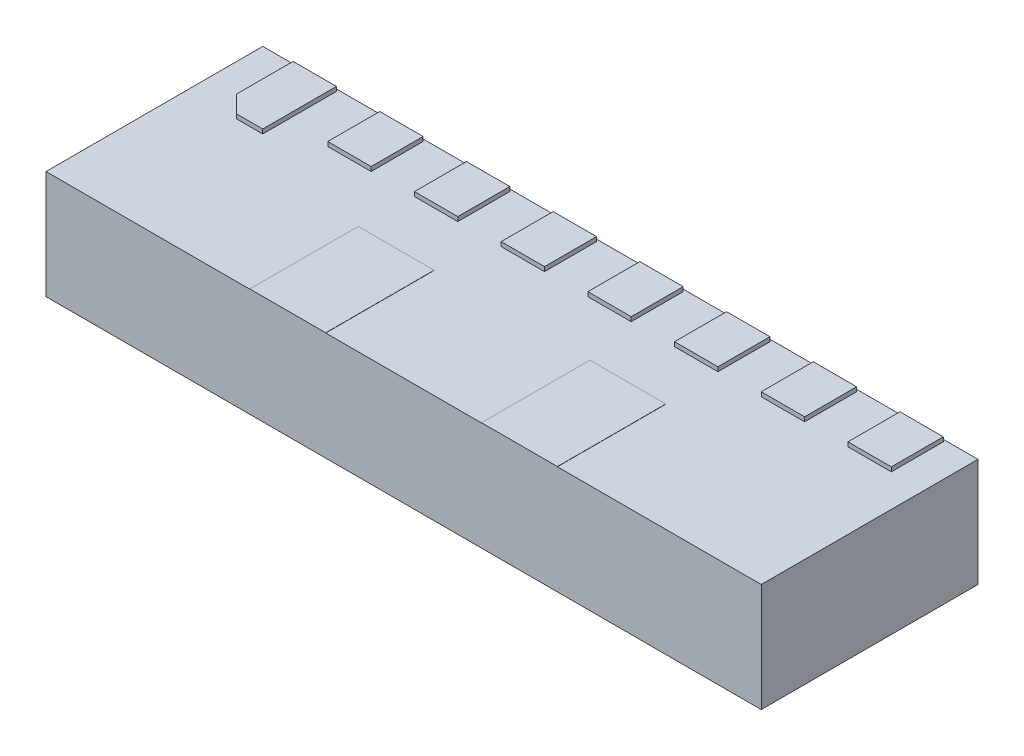
SolidWorks part; units mm, degrees
ref_plane "Front Plane" through (0, 0, 0) normal (0, 0, 1) x (1, 0, 0)
ref_plane "Top Plane" through (0, 0, 0) normal (0, 1, 0) x (1, 0, 0)
ref_plane "Right Plane" through (0, 0, 0) normal (1, 0, 0) x (0, 0, -1)
sketch "Sketch1" plane through (0, 0, 0) normal (0, 1, 0) x (1, 0, 0)
  line L1 (-1.65, 0.5) -> (1.65, 0.5)
  line L2 (-1.65, 0.5) -> (-1.65, -0.5)
  line L3 (-1.65, -0.5) -> (1.65, -0.5)
  line L4 (1.65, 0.5) -> (1.65, -0.5)
  line L5 (-1.65, 0.5) -> (1.65, -0.5) construction
  line L6 (-1.65, -0.5) -> (1.65, 0.5) construction
  point P0 (0, 0)
  dimension "D1" = 3.3
  dimension "D2" = 1
extrude "Boss-Extrude1" add sketch "Sketch1" along normal blind 0.5
sketch "Sketch2" plane through (0, 0.5, 0) normal (0, 1, 0) x (1, 0, 0)
  line L0 (0, 1.1724) -> (0, -1.0782) construction
  line L1 (-2.0344, 0) -> (2.5888, 0) construction
  line L2 (-1.65, -0.5) -> (1.65, -0.5) construction
  line L3 (-1.65, -0.5) -> (1.65, -0.5) construction
  line L4 (-0.595, 0.7012) -> (-0.595, -1.0172) construction
  line L5 (0.595, 0.7012) -> (0.595, -0.5257) construction
  line L6 (0.3594, -0.5) -> (0.7094, -0.5)
  line L7 (-0.7094, -0.5) -> (-0.7094, 0)
  line L8 (0.3594, -0.5) -> (0.3594, 0)
  line L9 (0.3594, 0) -> (0.7094, 0)
  line L10 (0.7094, -0.5) -> (0.7094, 0)
  line L11 (0.5835, -0.5) -> (0.7094, 0) construction
  line L12 (0.3594, 0) -> (0.595, -0.5257) construction
  line L13 (-0.3594, -0.5) -> (-0.7094, -0.5)
  line L14 (-0.3594, -0.5) -> (-0.3594, 0)
  line L15 (-0.3594, 0) -> (-0.7094, 0)
  point P11 (0.5835, -0.5)
  dimension "D1" = 0.5
  dimension "D2" = 0.595
  dimension "D3" = 0.595
  dimension "D4" = 0.35
extrude "Boss-Extrude2" add sketch "Sketch2" along normal blind 0.001
sketch "Sketch3" plane through (0, 0.5, 0) normal (0, 1, 0) x (1, 0, 0)
  line L0 (0, 1.0726) -> (0, -1.178) construction
  line L1 (-2.0289, 0) -> (2.2229, 0) construction
  line L2 (0.5, 0.49) -> (0.7, 0.49)
  line L3 (0.1, 0.49) -> (0.3, 0.49)
  line L4 (0.1, 0.49) -> (0.1, 0.25)
  line L5 (0.1, 0.25) -> (0.3, 0.25)
  line L6 (0.3, 0.49) -> (0.3, 0.25)
  line L7 (0.2, 0.6575) -> (0.2, 0.2208) construction
  line L8 (1.65, 0.5) -> (-1.65, 0.5) construction
  line L9 (0.7, 0.49) -> (0.7, 0.25)
  line L10 (0.5, 0.25) -> (0.7, 0.25)
  line L11 (0.5, 0.49) -> (0.5, 0.25)
  line L12 (0.9, 0.49) -> (1.1, 0.49)
  line L13 (1.1, 0.49) -> (1.1, 0.25)
  line L14 (0.9, 0.25) -> (1.1, 0.25)
  line L15 (0.9, 0.49) -> (0.9, 0.25)
  line L16 (1.3, 0.49) -> (1.5, 0.49)
  line L17 (1.5, 0.49) -> (1.5, 0.25)
  line L18 (1.3, 0.25) -> (1.5, 0.25)
  line L19 (1.3, 0.49) -> (1.3, 0.25)
  line L20 (-0.1, 0.49) -> (-0.1, 0.25)
  line L21 (-0.1, 0.49) -> (-0.3, 0.49)
  line L22 (-0.3, 0.49) -> (-0.3, 0.25)
  line L23 (-0.1, 0.25) -> (-0.3, 0.25)
  line L24 (-0.2, 0.6063) -> (-0.2, 0.1221) construction
  line L25 (-0.5, 0.49) -> (-0.7, 0.49)
  line L26 (-0.5, 0.49) -> (-0.5, 0.25)
  line L27 (-0.5, 0.25) -> (-0.7, 0.25)
  line L28 (-0.7, 0.49) -> (-0.7, 0.25)
  line L29 (-0.9, 0.49) -> (-1.1, 0.49)
  line L30 (-0.9, 0.49) -> (-0.9, 0.25)
  line L31 (-0.9, 0.25) -> (-1.1, 0.25)
  line L32 (-1.1, 0.49) -> (-1.1, 0.25)
  point P11 (0.2, 0.49)
  dimension "D1" = 0.2
  dimension "D2" = 0.25
  dimension "D3" = 0.01
  dimension "D4" = 0.2
  dimension "D6" = 3
  dimension "D5" = 4
extrude "Boss-Extrude3" add sketch "Sketch3" along normal blind 0.02
sketch "Sketch4" plane through (0, 0.5, 0) normal (0, 1, 0) x (1, 0, 0)
  line L0 (0, 0.8382) -> (0, -0.7912) construction
sketch "Sketch5" plane through (0, 0.52, 0) normal (0, 1, 0) x (1, 0, 0)
  line L0 (-1, 0.7346) -> (-1, -0.0406) construction
sketch "Sketch6" plane through (0, 0.5, 0) normal (0, 1, 0) x (1, 0, 0)
  line L0 (-1.4, 0.7103) -> (-1.4, -0.249) construction
  line L1 (-1.5, 0.49) -> (-1.3, 0.49)
  line L2 (-1.5, 0.49) -> (-1.5, 0.2297)
  line L3 (-1.4203, 0.15) -> (-1.3, 0.15)
  line L4 (-1.3, 0.49) -> (-1.3, 0.15)
  line L5 (-1, 0.7346) -> (-1, -0.0406) construction
  line L6 (1.65, 0.5) -> (-1.65, 0.5) construction
  line L7 (-1.5, 0.2297) -> (-1.4203, 0.15)
  point P8 (-1.4, 0.49)
  dimension "D1" = 0.4
  dimension "D2" = 45
  dimension "D3" = 0.01
  dimension "D4" = 0.35
  dimension "D5" = 0.2
extrude "Boss-Extrude4" add sketch "Sketch6" along normal blind 0.02
sketch "Sketch11" plane through (0, 0, -0.5) normal (0, 0, -1) x (-1, 0, 0)
  line L2 (0.1, 0.52) -> (0.3, 0.52) construction
  line L3 (0.1, 0.495) -> (0.3, 0.495)
  line L4 (0.1, 0.495) -> (0.1, 0.39)
  line L5 (0.1, 0.39) -> (0.3, 0.39)
  line L6 (0.3, 0.495) -> (0.3, 0.39)
  line L7 (0, -0.1597) -> (0, 1.0598) construction
  line L8 (-0.3, 0.495) -> (-0.3, 0.39)
  line L9 (-0.1, 0.39) -> (-0.3, 0.39)
  line L10 (-0.1, 0.495) -> (-0.1, 0.39)
  line L11 (-0.1, 0.495) -> (-0.3, 0.495)
  line L12 (0.5, 0.495) -> (0.7, 0.495)
  line L13 (0.7, 0.495) -> (0.7, 0.39)
  line L14 (0.5, 0.39) -> (0.7, 0.39)
  line L15 (0.5, 0.495) -> (0.5, 0.39)
  line L16 (0.9, 0.495) -> (1.1, 0.495)
  line L17 (1.1, 0.495) -> (1.1, 0.39)
  line L18 (0.9, 0.39) -> (1.1, 0.39)
  line L19 (0.9, 0.495) -> (0.9, 0.39)
  line L20 (1.3, 0.495) -> (1.5, 0.495)
  line L21 (1.5, 0.495) -> (1.5, 0.39)
  line L22 (1.3, 0.39) -> (1.5, 0.39)
  line L23 (1.3, 0.495) -> (1.3, 0.39)
  line L24 (-0.5, 0.495) -> (-0.7, 0.495)
  line L25 (-0.7, 0.495) -> (-0.7, 0.39)
  line L26 (-0.5, 0.495) -> (-0.5, 0.39)
  line L27 (-0.5, 0.39) -> (-0.7, 0.39)
  line L28 (-0.9, 0.495) -> (-1.1, 0.495)
  line L29 (-1.1, 0.495) -> (-1.1, 0.39)
  line L30 (-0.9, 0.495) -> (-0.9, 0.39)
  line L31 (-0.9, 0.39) -> (-1.1, 0.39)
  line L32 (-1.3, 0.495) -> (-1.5, 0.495)
  line L33 (-1.5, 0.495) -> (-1.5, 0.39)
  line L34 (-1.3, 0.495) -> (-1.3, 0.39)
  line L35 (-1.3, 0.39) -> (-1.5, 0.39)
  dimension "D1" = 0.13
  dimension "D2" = 0.105
  dimension "D3" = 4
  dimension "D4" = 4
extrude "Boss-Extrude5" add sketch "Sketch11" along normal blind 0.001
